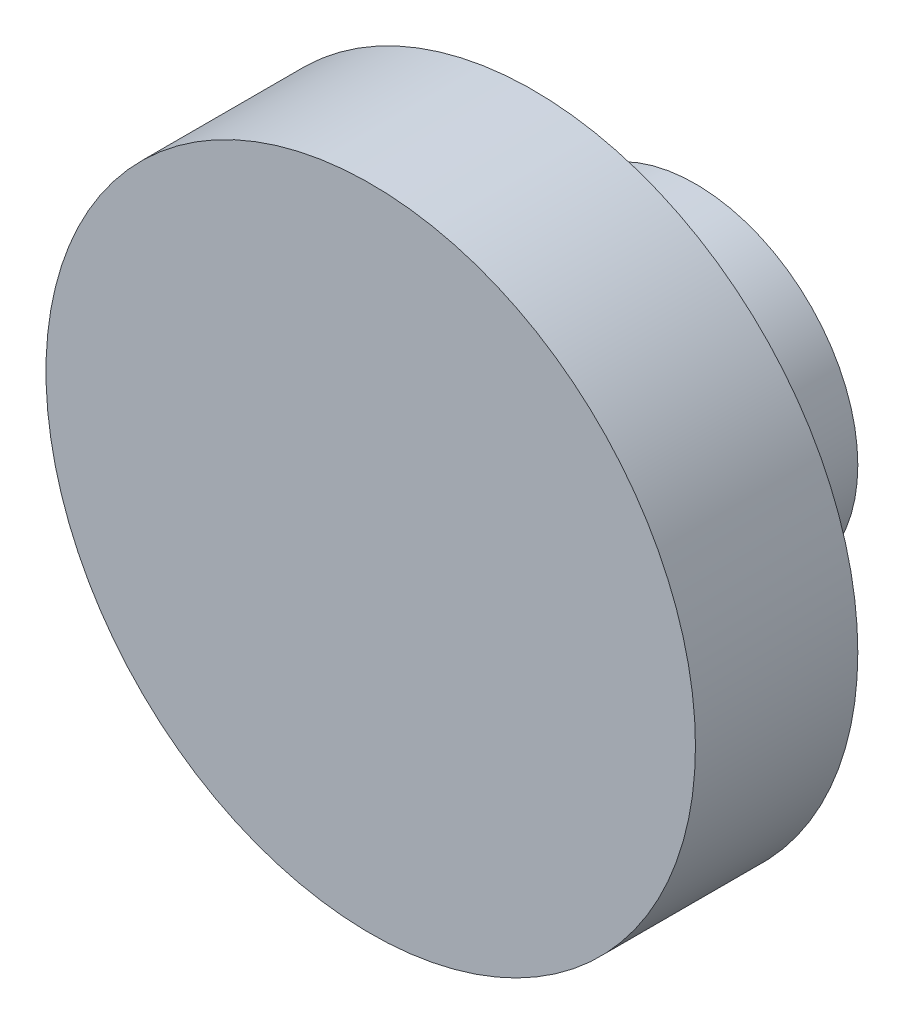
SolidWorks part; units mm, degrees
ref_plane "Front Plane" through (0, 0, 0) normal (0, 0, 1) x (1, 0, 0)
ref_plane "Top Plane" through (0, 0, 0) normal (0, 1, 0) x (1, 0, 0)
ref_plane "Right Plane" through (0, 0, 0) normal (1, 0, 0) x (0, 0, -1)
sketch "Sketch1" plane through (0, 0, 0) normal (0, 0, 1) x (1, 0, 0)
  circle A0 centre (0, 0) radius 15
  circle A1 centre (0, 0) radius 7.5
extrude "Boss-Extrude1" add sketch "Sketch1" along normal blind 15
sketch "Sketch2" plane through (0, 0, 15) normal (0, 0, 1) x (1, 0, 0)
  circle A0 centre (0, 0) radius 30
extrude "Boss-Extrude2" add sketch "Sketch2" along normal blind 15
